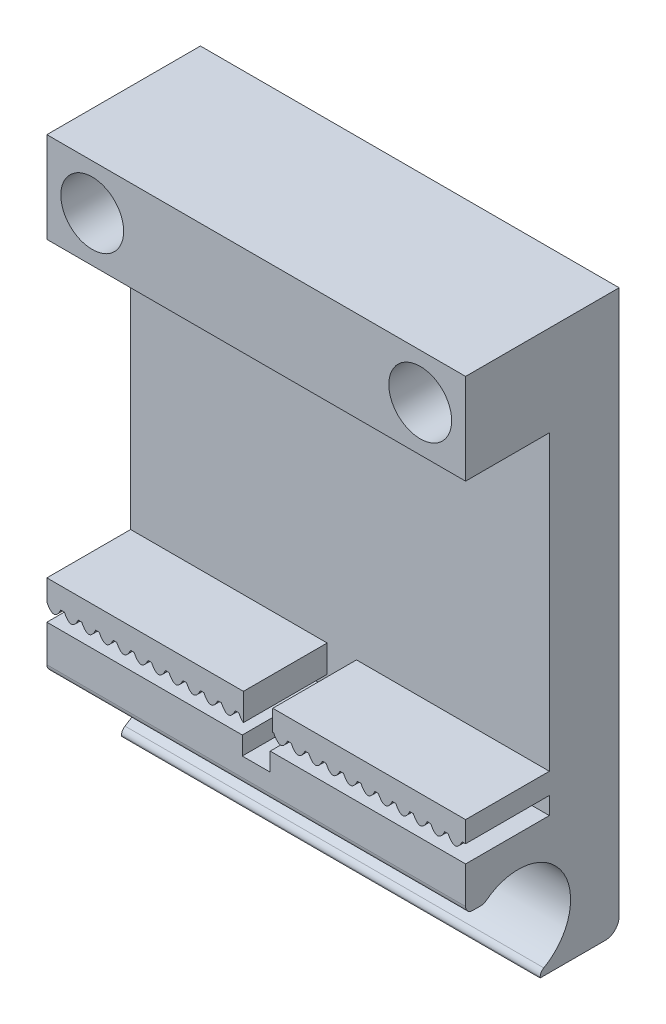
SolidWorks part; units mm, degrees
ref_plane "정면" through (0, 0, 0) normal (0, 0, 1) x (1, 0, 0)
ref_plane "윗면" through (0, 0, 0) normal (0, 1, 0) x (1, 0, 0)
ref_plane "우측면" through (0, 0, 0) normal (1, 0, 0) x (0, 0, -1)
sketch "스케치1" plane through (0, 0, 0) normal (0, 0, 1) x (1, 0, 0)
  line L1 (0, 0) -> (-60, 0)
  line L2 (0, 0) -> (0, 80)
  line L3 (0, 80) -> (-60, 80)
  line L4 (-60, 0) -> (-60, 80)
  dimension "D1" = 60
  dimension "D2" = 80
extrude "보스-돌출1" add sketch "스케치1" along normal blind 10
sketch "스케치2" plane through (0, 0, 10) normal (0, 0, 1) x (1, 0, 0)
  line L0 (0, 0) -> (0, 80) construction
  line L1 (-60, 80) -> (0, 80)
  line L2 (-60, 80) -> (-60, 67)
  line L3 (-60, 67) -> (0, 67)
  line L4 (0, 80) -> (0, 67)
  circle A0 centre (-6.5, 73.5) radius 4
  circle A1 centre (-53.5, 73.5) radius 4
  dimension "D2" = 6.5
  dimension "D3" = 6.5
  dimension "D4" = 6.5
  dimension "D1" = 13
extrude "보스-돌출2" add sketch "스케치2" along normal blind 12
sketch "스케치3" plane through (0, 0, 10) normal (0, 0, 1) x (1, 0, 0)
  line L0 (0, 0) -> (0, 67) construction
  line L1 (-60, 0) -> (0, 0)
  line L2 (-60, 0) -> (-60, 20)
  line L3 (-60, 20) -> (0, 20)
  line L4 (0, 0) -> (0, 20)
  dimension "D1" = 20
extrude "보스-돌출3" add sketch "스케치3" along normal blind 12
sketch "스케치6" plane through (0, 0, 0) normal (1, 0, 0) x (0, 0, -1)
  circle A0 centre (-14.4537, 7.5501) radius 7.5
extrude "컷-돌출1" cut sketch "스케치6" against normal blind 60
sketch "스케치7" plane through (0, 0, 0) normal (1, 0, 0) x (0, 0, -1)
  line L0 (-22, 7.7525) -> (-22, 0)
  line L1 (-22, 0) -> (-22, 20) construction
sketch "스케치8" plane through (0, 0, 0) normal (1, 0, 0) x (0, 0, -1)
  line L0 (-14.2542, 0) -> (-22, 0)
  line L1 (-22, 0) -> (0, 0) construction
  line L2 (-22, 0) -> (-22, 7.7525)
  line L3 (-22, 7.7525) -> (-14.2542, 0)
extrude "컷-돌출3" cut sketch "스케치8" against normal blind 60
sketch "스케치9" plane through (0, 0, 0) normal (1, 0, 0) x (0, 0, -1)
  line L0 (-19.3678, 13.216) -> (-22, 13.216)
  line L1 (-22, 7.7525) -> (-22, 20) construction
  line L2 (-22, 13.216) -> (-22, 7.7525)
  line L3 (-22, 7.7525) -> (-19.3678, 13.216)
  line L5 (-14.2542, 0) -> (0, 0) construction
  line L7 (-11.3118, 0.74) -> (-11.3118, 0)
  line L8 (-11.3118, 0.74) -> (-11.3118, 0.8256)
  line L9 (-11.3118, 0.8256) -> (-14.6498, 0)
  line L10 (-14.6498, 0) -> (-11.3118, 0)
  arc A0 (-14.3058, 0.0516) -> (-21.9521, 7.7046) centre (-14.4537, 7.5501) ccw construction
sketch "스케치10" plane through (0, 0, 0) normal (1, 0, 0) x (0, 0, -1)
  line L0 (-19.3678, 13.216) -> (-22, 13.216)
  line L1 (-22, 13.216) -> (-22, 7.4759)
  line L2 (-22, 7.7525) -> (-22, 0) construction
  line L3 (-22, 7.4759) -> (-19.3678, 13.216)
  line L4 (-11.3118, 0) -> (-15.1355, 0)
  line L5 (-15.1355, 0) -> (-11.3118, 1.4319)
  line L6 (-11.3118, 1.4319) -> (-11.3118, 0)
extrude "컷-돌출6" cut sketch "스케치10" against normal blind 60
fillet "필렛11" radius 1 3 edges at (-30, 13.216, 22) (-30, 13.216, 19.3678) (-30, 0.74, 11.3118)
sketch "스케치11" plane through (0, 0, 10) normal (0, 0, 1) x (1, 0, 0)
  line L0 (-60, 67) -> (-60, 20) construction
  line L1 (-60, 21.5) -> (0, 21.5)
  line L2 (-60, 21.5) -> (-60, 25)
  line L3 (-60, 25) -> (0, 25)
  line L4 (0, 21.5) -> (0, 25)
  line L5 (0, 20) -> (0, 67) construction
  line L6 (0, 20) -> (-60, 20) construction
  dimension "D1" = 1.5
  dimension "D2" = 3.5
extrude "보스-돌출4" add sketch "스케치11" along normal blind 12
sketch "스케치13" plane through (0, 0, 22) normal (0, 0, 1) x (1, 0, 0)
  line L0 (-60, 20) -> (-60, 14.216) construction
  line L1 (-32, 18.3877) -> (-28, 18.3877)
  line L2 (-32, 18.3877) -> (-32, 16.8877)
  line L3 (-32, 16.8877) -> (-28, 16.8877)
  line L4 (-28, 18.3877) -> (-28, 16.8877)
  line L5 (0, 14.216) -> (0, 20) construction
  point P4 (-32, 17.6377)
  dimension "D1" = 28
  dimension "D2" = 28
sketch "스케치14" plane through (0, 0, 22) normal (0, 0, 1) x (1, 0, 0)
  line L0 (-32, 16.8877) -> (-32, 18.3877)
  line L1 (-32, 18.3877) -> (-28, 18.3877)
  line L2 (-28, 18.3877) -> (-28, 16.8877)
  line L3 (-28, 16.8877) -> (-32, 16.8877)
extrude "컷-돌출8" cut sketch "스케치14" against normal blind 22
fillet "필렛12" radius 2 1 edges at (-30, 0, 0)
sketch "스케치15" plane through (-60, 0, 0) normal (-1, 0, 0) x (0, 0, 1)
  line L0 (22, 25) -> (22, 21.5) construction
  line L1 (10, 21.5) -> (22, 21.5)
  line L2 (10, 21.5) -> (10, 22)
  line L3 (10, 22) -> (22, 22)
  line L4 (22, 21.5) -> (22, 22)
  dimension "D1" = 0.5
extrude "컷-돌출9" cut sketch "스케치15" against normal through all
sketch "스케치17" plane through (0, 0, 22) normal (0, 0, 1) x (1, 0, 0)
  line L0 (-60, 20) -> (-60, 21)
  line L1 (-60, 22) -> (-60, 20) construction
  line L2 (-60, 21) -> (-4.2919, 21)
  line L3 (-4.2919, 21) -> (-4.2919, 20)
  line L4 (0, 20) -> (-60, 20) construction
  line L5 (0, 22) -> (-60, 22) construction
  line L6 (-60, 22) -> (-58.0632, 22)
  line L7 (-57.5, 22) -> (-55.5632, 22)
  line L8 (-55, 22) -> (-53.0632, 22)
  line L9 (-52.5, 22) -> (-50.5632, 22)
  line L10 (-50, 22) -> (-48.0632, 22)
  line L11 (-47.5, 22) -> (-45.5632, 22)
  line L12 (-45, 22) -> (-43.0632, 22)
  line L13 (-42.5, 22) -> (-40.5632, 22)
  line L14 (-40, 22) -> (-38.0632, 22)
  line L15 (-37.5, 22) -> (-35.5632, 22)
  line L16 (-35, 22) -> (-33.0632, 22)
  line L17 (-32.5, 22) -> (-30.5632, 22)
  line L18 (-30, 22) -> (-28.0632, 22)
  line L19 (-27.5, 22) -> (-25.5632, 22)
  line L20 (-25, 22) -> (-23.0632, 22)
  line L21 (-22.5, 22) -> (-20.5632, 22)
  line L22 (-20, 22) -> (-18.0632, 22)
  line L23 (-17.5, 22) -> (-15.5632, 22)
  line L24 (-15, 22) -> (-13.0632, 22)
  line L25 (-12.5, 22) -> (-10.5632, 22)
  line L26 (-10, 22) -> (-8.0632, 22)
  line L27 (-7.5, 22) -> (-5.5632, 22)
  line L28 (-5, 22) -> (-3.0632, 22)
  line L29 (-2.5, 22) -> (-0.5632, 22)
  spline S0 degree 2 poles (-60, 22) (-59.0652, 19.9995) (-58.0632, 22) knots 0 0 0 1 1 1
  spline S1 degree 2 poles (-57.5, 22) (-56.5652, 19.9995) (-55.5632, 22) knots 0 0 0 1 1 1
  spline S2 degree 2 poles (-55, 22) (-54.0652, 19.9995) (-53.0632, 22) knots 0 0 0 1 1 1
  spline S3 degree 2 poles (-52.5, 22) (-51.5652, 19.9995) (-50.5632, 22) knots 0 0 0 1 1 1
  spline S4 degree 2 poles (-50, 22) (-49.0652, 19.9995) (-48.0632, 22) knots 0 0 0 1 1 1
  spline S5 degree 2 poles (-47.5, 22) (-46.5652, 19.9995) (-45.5632, 22) knots 0 0 0 1 1 1
  spline S6 degree 2 poles (-45, 22) (-44.0652, 19.9995) (-43.0632, 22) knots 0 0 0 1 1 1
  spline S7 degree 2 poles (-42.5, 22) (-41.5652, 19.9995) (-40.5632, 22) knots 0 0 0 1 1 1
  spline S8 degree 2 poles (-40, 22) (-39.0652, 19.9995) (-38.0632, 22) knots 0 0 0 1 1 1
  spline S9 degree 2 poles (-37.5, 22) (-36.5652, 19.9995) (-35.5632, 22) knots 0 0 0 1 1 1
  spline S10 degree 2 poles (-35, 22) (-34.0652, 19.9995) (-33.0632, 22) knots 0 0 0 1 1 1
  spline S11 degree 2 poles (-32.5, 22) (-31.5652, 19.9995) (-30.5632, 22) knots 0 0 0 1 1 1
  spline S12 degree 2 poles (-30, 22) (-29.0652, 19.9995) (-28.0632, 22) knots 0 0 0 1 1 1
  spline S13 degree 2 poles (-27.5, 22) (-26.5652, 19.9995) (-25.5632, 22) knots 0 0 0 1 1 1
  spline S14 degree 2 poles (-25, 22) (-24.0652, 19.9995) (-23.0632, 22) knots 0 0 0 1 1 1
  spline S15 degree 2 poles (-22.5, 22) (-21.5652, 19.9995) (-20.5632, 22) knots 0 0 0 1 1 1
  spline S16 degree 2 poles (-20, 22) (-19.0652, 19.9995) (-18.0632, 22) knots 0 0 0 1 1 1
  spline S17 degree 2 poles (-17.5, 22) (-16.5652, 19.9995) (-15.5632, 22) knots 0 0 0 1 1 1
  spline S18 degree 2 poles (-15, 22) (-14.0652, 19.9995) (-13.0632, 22) knots 0 0 0 1 1 1
  spline S19 degree 2 poles (-12.5, 22) (-11.5652, 19.9995) (-10.5632, 22) knots 0 0 0 1 1 1
  spline S20 degree 2 poles (-10, 22) (-9.0652, 19.9995) (-8.0632, 22) knots 0 0 0 1 1 1
  spline S21 degree 2 poles (-7.5, 22) (-6.5652, 19.9995) (-5.5632, 22) knots 0 0 0 1 1 1
  spline S22 degree 2 poles (-5, 22) (-4.0652, 19.9995) (-3.0632, 22) knots 0 0 0 1 1 1
  spline S23 degree 2 poles (-2.5, 22) (-1.5652, 19.9995) (-0.5632, 22) knots 0 0 0 1 1 1
  dimension "D1" = 24
sketch "스케치18" plane through (0, 0, 22) normal (0, 0, 1) x (1, 0, 0)
  line L0 (0, 22) -> (-60, 22) construction
  line L1 (-60, 22) -> (-58, 22)
  line L2 (-57.5, 22) -> (-55.5, 22)
  line L3 (-55, 22) -> (-53, 22)
  line L4 (-52.5, 22) -> (-50.5, 22)
  line L5 (-50, 22) -> (-48, 22)
  line L6 (-47.5, 22) -> (-45.5, 22)
  line L7 (-45, 22) -> (-43, 22)
  line L8 (-42.5, 22) -> (-40.5, 22)
  line L9 (-40, 22) -> (-38, 22)
  line L10 (-37.5, 22) -> (-35.5, 22)
  line L11 (-35, 22) -> (-33, 22)
  line L12 (-32.5, 22) -> (-30.5, 22)
  line L13 (-30, 22) -> (-28, 22)
  line L14 (-27.5, 22) -> (-25.5, 22)
  line L15 (-25, 22) -> (-23, 22)
  line L16 (-22.5, 22) -> (-20.5, 22)
  line L17 (-20, 22) -> (-18, 22)
  line L18 (-17.5, 22) -> (-15.5, 22)
  line L19 (-15, 22) -> (-13, 22)
  line L20 (-12.5, 22) -> (-10.5, 22)
  line L21 (-10, 22) -> (-8, 22)
  line L22 (-7.5, 22) -> (-5.5, 22)
  line L23 (-5, 22) -> (-3, 22)
  line L24 (-2.5, 22) -> (-0.5, 22)
  spline S0 degree 2 poles (-60, 22) (-59, 20) (-58, 22) knots 0 0 0 1 1 1
  spline S1 degree 2 poles (-57.5, 22) (-56.5, 20) (-55.5, 22) knots 0 0 0 1 1 1
  spline S2 degree 2 poles (-55, 22) (-54, 20) (-53, 22) knots 0 0 0 1 1 1
  spline S3 degree 2 poles (-52.5, 22) (-51.5, 20) (-50.5, 22) knots 0 0 0 1 1 1
  spline S4 degree 2 poles (-50, 22) (-49, 20) (-48, 22) knots 0 0 0 1 1 1
  spline S5 degree 2 poles (-47.5, 22) (-46.5, 20) (-45.5, 22) knots 0 0 0 1 1 1
  spline S6 degree 2 poles (-45, 22) (-44, 20) (-43, 22) knots 0 0 0 1 1 1
  spline S7 degree 2 poles (-42.5, 22) (-41.5, 20) (-40.5, 22) knots 0 0 0 1 1 1
  spline S8 degree 2 poles (-40, 22) (-39, 20) (-38, 22) knots 0 0 0 1 1 1
  spline S9 degree 2 poles (-37.5, 22) (-36.5, 20) (-35.5, 22) knots 0 0 0 1 1 1
  spline S10 degree 2 poles (-35, 22) (-34, 20) (-33, 22) knots 0 0 0 1 1 1
  spline S11 degree 2 poles (-32.5, 22) (-31.5, 20) (-30.5, 22) knots 0 0 0 1 1 1
  spline S12 degree 2 poles (-30, 22) (-29, 20) (-28, 22) knots 0 0 0 1 1 1
  spline S13 degree 2 poles (-27.5, 22) (-26.5, 20) (-25.5, 22) knots 0 0 0 1 1 1
  spline S14 degree 2 poles (-25, 22) (-24, 20) (-23, 22) knots 0 0 0 1 1 1
  spline S15 degree 2 poles (-22.5, 22) (-21.5, 20) (-20.5, 22) knots 0 0 0 1 1 1
  spline S16 degree 2 poles (-20, 22) (-19, 20) (-18, 22) knots 0 0 0 1 1 1
  spline S17 degree 2 poles (-17.5, 22) (-16.5, 20) (-15.5, 22) knots 0 0 0 1 1 1
  spline S18 degree 2 poles (-15, 22) (-14, 20) (-13, 22) knots 0 0 0 1 1 1
  spline S19 degree 2 poles (-12.5, 22) (-11.5, 20) (-10.5, 22) knots 0 0 0 1 1 1
  spline S20 degree 2 poles (-10, 22) (-9, 20) (-8, 22) knots 0 0 0 1 1 1
  spline S21 degree 2 poles (-7.5, 22) (-6.5, 20) (-5.5, 22) knots 0 0 0 1 1 1
  spline S22 degree 2 poles (-5, 22) (-4, 20) (-3, 22) knots 0 0 0 1 1 1
  spline S23 degree 2 poles (-2.5, 22) (-1.5, 20) (-0.5, 22) knots 0 0 0 1 1 1
  dimension "D1" = 24
extrude "보스-돌출5" add sketch "스케치18" against normal blind 20
sketch "스케치19" plane through (0, 0, 22) normal (0, 0, 1) x (1, 0, 0)
  line L0 (0, 14.216) -> (0, 20) construction
  line L1 (-60, 20) -> (0, 20)
  line L2 (-60, 20) -> (-60, 19.5)
  line L3 (-60, 19.5) -> (0, 19.5)
  line L4 (0, 20) -> (0, 19.5)
  line L5 (0, 25) -> (-60, 25) construction
  line L6 (-31.8375, 25) -> (-27.6347, 25)
  line L7 (-31.8375, 25) -> (-31.8375, 21)
  line L8 (-31.8375, 21) -> (-27.6347, 21)
  line L9 (-27.6347, 25) -> (-27.6347, 21)
  dimension "D1" = 0.5
extrude "컷-돌출10" cut sketch "스케치19" against normal blind 12
sketch "스케치20" plane through (0, 0, 22) normal (0, 0, 1) x (1, 0, 0)
  line L0 (-60, 19.5) -> (0, 19.5) construction
  line L1 (-32, 18.3877) -> (-28, 18.3877)
  line L2 (-32, 18.3877) -> (-32, 19.5)
  line L3 (-32, 19.5) -> (-28, 19.5)
  line L4 (-28, 18.3877) -> (-28, 19.5)
  dimension "D1" = 4
sketch "스케치21" plane through (0, 0, 22) normal (0, 0, 1) x (1, 0, 0)
  line L1 (-32, 19.5) -> (-28, 19.5)
  line L2 (-32, 19.5) -> (-32, 18.3877)
  line L3 (-32, 18.3877) -> (-28, 18.3877)
  line L4 (-28, 19.5) -> (-28, 18.3877)
extrude "컷-돌출12" cut sketch "스케치21" against normal through all
sketch "스케치22" plane through (0, 0, 22) normal (0, 0, 1) x (1, 0, 0)
  circle A0 centre (-53.5, 73.5) radius 4.5
  circle A1 centre (-6.5, 73.5) radius 4.5
extrude "컷-돌출14" cut sketch "스케치22" against normal blind 12
